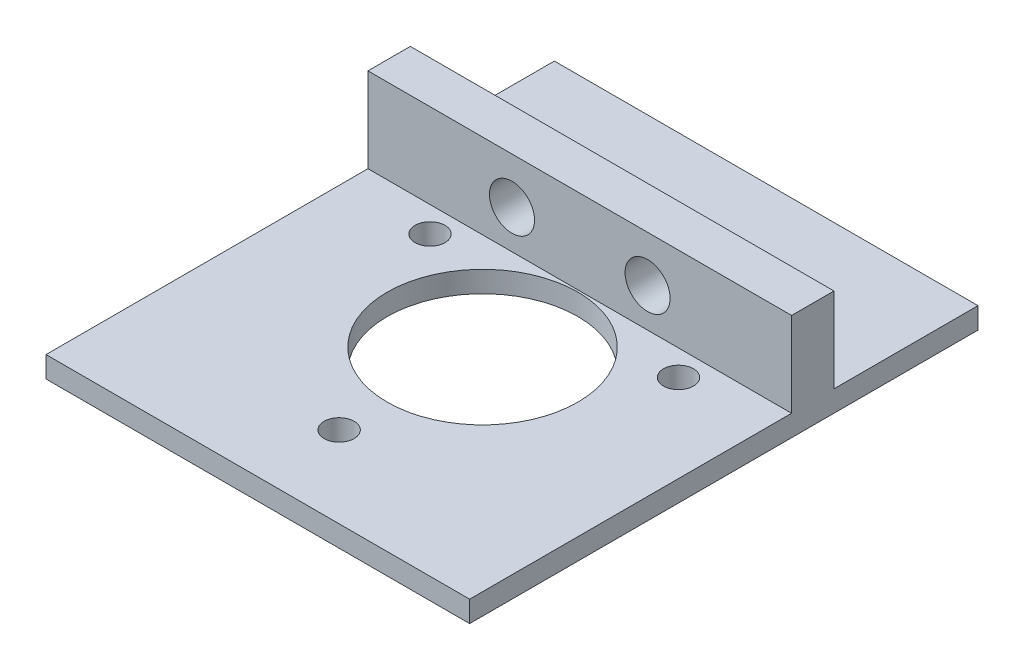
SolidWorks part; units mm, degrees
ref_plane "Front Plane" through (0, 0, 0) normal (0, 0, 1) x (1, 0, 0)
ref_plane "Top Plane" through (0, 0, 0) normal (0, 1, 0) x (1, 0, 0)
ref_plane "Right Plane" through (0, 0, 0) normal (1, 0, 0) x (0, 0, -1)
sketch "Sketch1" plane through (0, 0, 0) normal (1, 0, 0) x (0, 0, -1)
  line L0 (0, 0) -> (0, 3.175)
  line L1 (55, 0) -> (-55, 0) construction
  line L2 (0, 3.175) -> (48.26, 3.175)
  line L3 (48.26, 3.175) -> (48.26, 15.875)
  line L4 (48.26, 15.875) -> (54.61, 15.875)
  line L5 (54.61, 15.875) -> (54.61, 3.175)
  line L6 (54.61, 3.175) -> (76.2, 3.175)
  line L9 (76.2, 3.175) -> (76.2, 0)
  line L10 (76.2, 0) -> (0, 0)
  line L11 (0, 55) -> (0, -55) construction
  point P9 (76.2, 3.175)
  point P11 (0, 1.5875)
  point P12 (0, 0)
  point P13 (0, 0)
  point P16 (0, 0)
  dimension "D1" = 48.26
  dimension "D2" = 3.175
  dimension "D3" = 12.7
  dimension "D4" = 76.2
  dimension "D6" = 6.35
extrude "Boss-Extrude1" add sketch "Sketch1" along normal blind 63.5
sketch "Sketch2" plane through (0, 3.175, 0) normal (0, 1, 0) x (1, 0, 0)
  circle A0 centre (31.75, 33.6856) radius 14.2875
  dimension "D1" = 28.575
extrude "Cut-Extrude1" cut sketch "Sketch2" against normal through all
sketch "Sketch4" plane through (0, 0, 0) normal (0, -1, 0) x (-1, 0, 0)
  point P0 (-31.75, 12.1856)
  point P1 (-13.1305, 44.4356)
  point P3 (-50.3695, 44.4356)
hole_wizard "M4 Clearance Hole1" positions "Sketch5" profile "Sketch7" hole size "M4" standard "ANSI Metric" end condition through all
sketch "Sketch5" plane through (0, 0, 0) normal (0, -1, 0) x (-1, 0, 0)
  point P0 (-31.75, 12.1856)
  point P3 (-50.3695, 44.4356)
  point P6 (-13.1305, 44.4356)
sketch "Sketch7" plane through (31.75, 0, -12.1856) normal (1, 0, 0) x (0, 0, -1)
  line L0 (0, 0) -> (0, 15.875)
  line L1 (0, 15.875) -> (2.25, 15.875)
  line L2 (2.25, 15.875) -> (2.25, 0)
  line L5 (2.25, 0) -> (0, 0)
  line L11 (0, -6.35) -> (0, 107.95) construction
  dimension "Thru Hole Dia." = 4.5
  dimension "Thru Hole Depth" = 15.875
sketch "Sketch8" plane through (0, 0, -48.26) normal (0, 0, 1) x (1, 0, 0)
  point P2 (41.91, 8.9662)
  point P5 (21.59, 8.9662)
hole_wizard "1/4 Clearance Hole1" positions "Sketch9" profile "Sketch10" hole size "1/4" standard "ANSI Inch" end condition through all
sketch "Sketch9" plane through (0, 0, -48.26) normal (0, 0, 1) x (1, 0, 0)
  point P6 (41.91, 8.9662)
  point P9 (21.59, 8.9662)
sketch "Sketch10" plane through (41.91, 8.9662, -48.26) normal (1, 0, 0) x (0, -1, 0)
  line L0 (0, 0) -> (0, 27.94)
  line L1 (0, 27.94) -> (3.3782, 27.94)
  line L2 (3.3782, 27.94) -> (3.3782, 0)
  line L5 (3.3782, 0) -> (0, 0)
  line L11 (0, -6.35) -> (0, 107.95) construction
  dimension "Thru Hole Dia." = 6.7564
  dimension "Thru Hole Depth" = 27.94
sketch "Sketch11" [suppressed] plane through (0, 3.175, 0) normal (0, 1, 0) x (1, 0, 0)
  line L0 (63.5, 0) -> (0, 0) construction
  line L1 (63.5, 69.85) -> (0, 69.85) construction
  line L2 (0, 48.26) -> (0, 0) construction
  line L3 (63.5, 48.26) -> (63.5, 0) construction
  point P0 (6.35, 6.35)
  point P1 (53.34, 6.35)
  point P2 (6.35, 59.055)
  point P3 (53.34, 59.055)
  dimension "D1" = 6.35
  dimension "D2" = 10.795
  dimension "D3" = 6.35
  dimension "D4" = 10.16
hole_wizard "#8 Clearance Hole1" [suppressed] positions "Sketch12" profile "Sketch13" hole size "#8" standard "ANSI Inch"
sketch "Sketch12" [suppressed] plane through (0, 3.175, 0) normal (0, 1, 0) x (1, 0, 0)
  point P0 (6.35, 6.35)
  point P3 (53.34, 6.35)
  point P6 (6.35, 59.055)
  point P9 (53.34, 59.055)
sketch "Sketch13" plane through (6.35, 3.175, -6.35) normal (1, 0, 0) x (0, 0, 1)
  line L0 (0, 0) -> (0, 3.175)
  line L1 (0, 3.175) -> (2.2479, 3.175)
  line L2 (2.2479, 3.175) -> (2.2479, 0)
  line L5 (2.2479, 0) -> (0, 0)
  line L11 (0, -6.35) -> (0, 107.95) construction
  dimension "Thru Hole Dia." = 4.4958
  dimension "Thru Hole Depth" = 3.175
